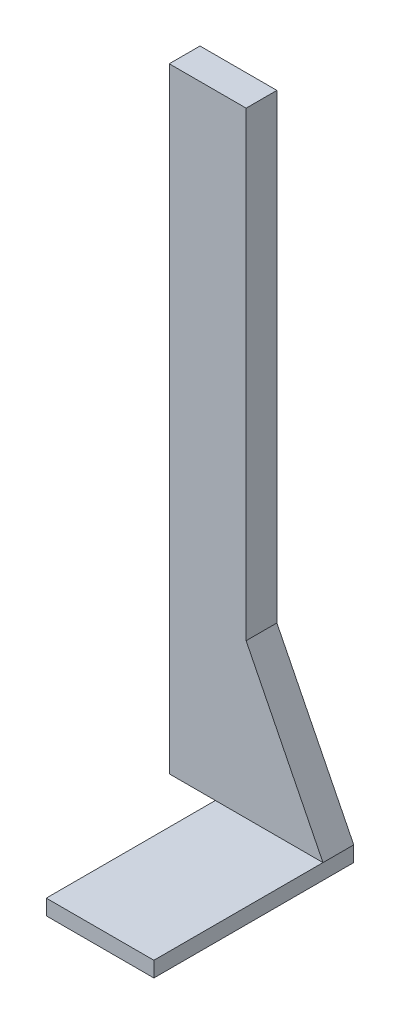
SolidWorks part; units mm, degrees
ref_plane "Front Plane" through (0, 0, 0) normal (0, 0, 1) x (1, 0, 0)
ref_plane "Top Plane" through (0, 0, 0) normal (0, 1, 0) x (1, 0, 0)
ref_plane "Right Plane" through (0, 0, 0) normal (1, 0, 0) x (0, 0, -1)
sketch "Sketch1" plane through (0, 0, 0) normal (0, 1, 0) x (1, 0, 0)
  line L0 (-35, 0) -> (-35, -65)
  line L1 (0, 0) -> (-35, 0)
  line L2 (0, 0) -> (0, -65)
  line L3 (0, -65) -> (-35, -65)
  dimension "D1" = 65
  dimension "D2" = 35
extrude "Boss-Extrude1" add sketch "Sketch1" along normal blind 5
sketch "Sketch2" plane through (0, 0, 0) normal (0, 0, 1) x (1, 0, 0)
  line L0 (0, 5) -> (-25, 55)
  line L1 (-25, 55) -> (-25, 205)
  line L2 (-25, 205) -> (-50, 205)
  line L3 (0, 5) -> (-50, 5)
  line L4 (-50, 5) -> (-50, 205)
  line L5 (0, 5) -> (-50, 5)
  point P3 (-50, 5)
  dimension "D1" = 200
  dimension "D2" = 150
  dimension "D3" = 25
  dimension "D4" = 50
extrude "Boss-Extrude2" add sketch "Sketch2" along normal blind 10 contours L2 L4 L3 L0 L1
